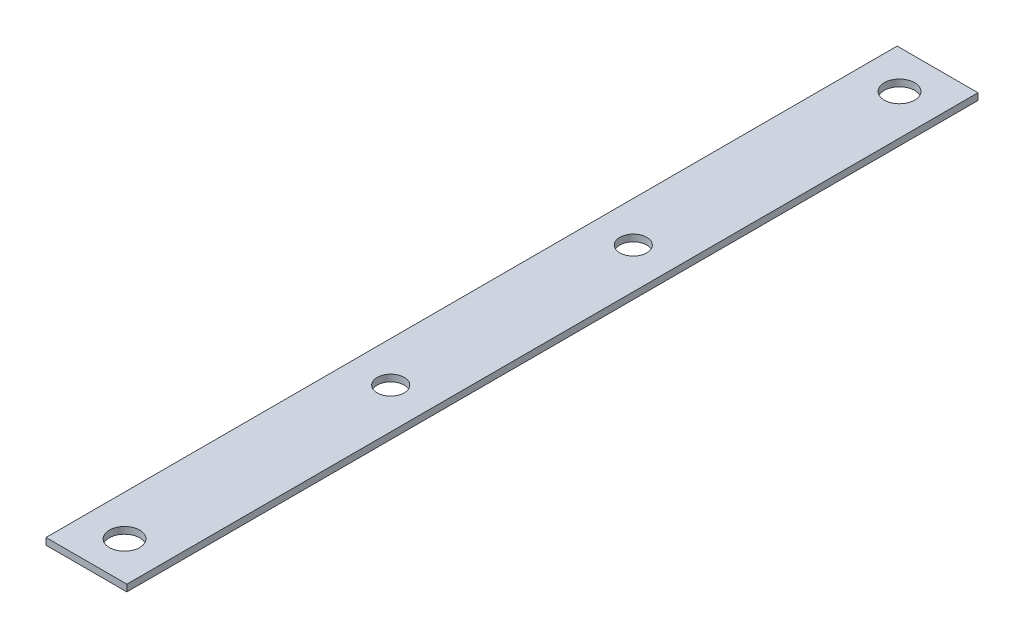
SolidWorks part; units mm, degrees
material "Plain Carbon Steel"
ref_plane "Front Plane" through (0, 0, 0) normal (0, 0, 1) x (1, 0, 0)
ref_plane "Top Plane" through (0, 0, 0) normal (0, 1, 0) x (1, 0, 0)
ref_plane "Right Plane" through (0, 0, 0) normal (1, 0, 0) x (0, 0, -1)
sketch "Sketch1" plane through (0, 0, 0) normal (0, 0, 1) x (1, 0, 0)
  line L1 (0, 0) -> (38.1, 0)
  line L2 (0, 0) -> (0, 3.175)
  line L3 (0, 3.175) -> (38.1, 3.175)
  line L4 (38.1, 0) -> (38.1, 3.175)
  dimension "D1" = 38.1
  dimension "D2" = 3.175
extrude "Boss-Extrude1" add sketch "Sketch1" along normal blind 401.0152
sketch "Sketch2" plane through (0, 3.175, 0) normal (0, 1, 0) x (1, 0, 0)
  line L0 (19.05, -383.0701) -> (19.05, -401.0152) construction
  line L1 (19.05, -17.9451) -> (19.05, -383.0701) construction
  line L2 (38.1, -401.0152) -> (0, -401.0152) construction
  line L3 (38.1, 0) -> (0, 0) construction
  line L4 (19.05, 0) -> (19.05, -144.6164) construction
  line L5 (38.1, -200.5076) -> (0, -200.5076) construction
  line L6 (38.1, -401.0152) -> (38.1, 0) construction
  line L7 (0, -401.0152) -> (0, 0) construction
  line L8 (19.05, -200.5076) -> (19.05, -257.6576) construction
  line L9 (19.05, -200.5076) -> (19.05, -143.3576) construction
  circle A0 centre (19.05, -383.0701) radius 7.1438
  circle A1 centre (19.05, -17.9451) radius 7.1438
  circle A2 centre (19.05, -257.6576) radius 6.35
  circle A3 centre (19.05, -143.3576) radius 6.35
  point P4 (19.05, -200.5076)
  point P11 (19.05, -144.6164)
  point P23 (19.05, -251.3076)
  dimension "D2" = 57.15
  dimension "D4" = 12.7
  dimension "D1" = 365.125
  dimension "D3" = 144.6164
  dimension "D5" = 57.15
extrude "Cut-Extrude1" cut sketch "Sketch2" against normal through all
